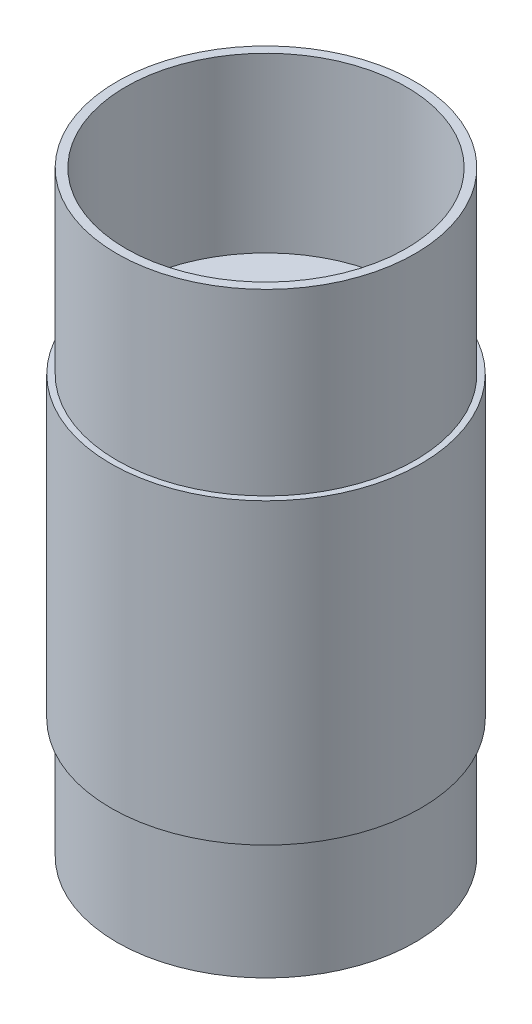
SolidWorks part; units mm, degrees
material "Plástico personalizado"
ref_plane "Plano frontal" through (0, 0, 0) normal (0, 0, 1) x (1, 0, 0)
ref_plane "Plano superior" through (0, 0, 0) normal (0, 1, 0) x (1, 0, 0)
ref_plane "Plano direito" through (0, 0, 0) normal (1, 0, 0) x (0, 0, -1)
sketch "Esboço1" plane through (0, 0, 0) normal (0, 1, 0) x (1, 0, 0)
  circle A0 centre (0, 0) radius 25
  circle A1 centre (0, 0) radius 23.5
extrude "Ressalto-extrusão1" add sketch "Esboço1" along normal blind 20 contours A1 | A0
sketch "Esboço2" plane through (0, 20, 0) normal (0, 1, 0) x (1, 0, 0)
  circle A0 centre (0, 0) radius 26
  circle A1 centre (0, 0) radius 25
extrude "Ressalto-extrusão2" add sketch "Esboço2" along normal blind 50 separate body contours A1 | A0
sketch "Esboço3" plane through (0, 70, 0) normal (0, 1, 0) x (1, 0, 0)
  circle A0 centre (0, 0) radius 23.5
  circle A1 centre (0, 0) radius 25
extrude "Ressalto-extrusão3" add sketch "Esboço3" along normal blind 30 separate body contours A1 | A0
sketch "Esboço18" plane through (0, 70, 0) normal (0, 1, 0) x (1, 0, 0)
  circle A0 centre (0, 0) radius 24
extrude "Ressalto-extrusão4" add sketch "Esboço18" along normal blind 1
